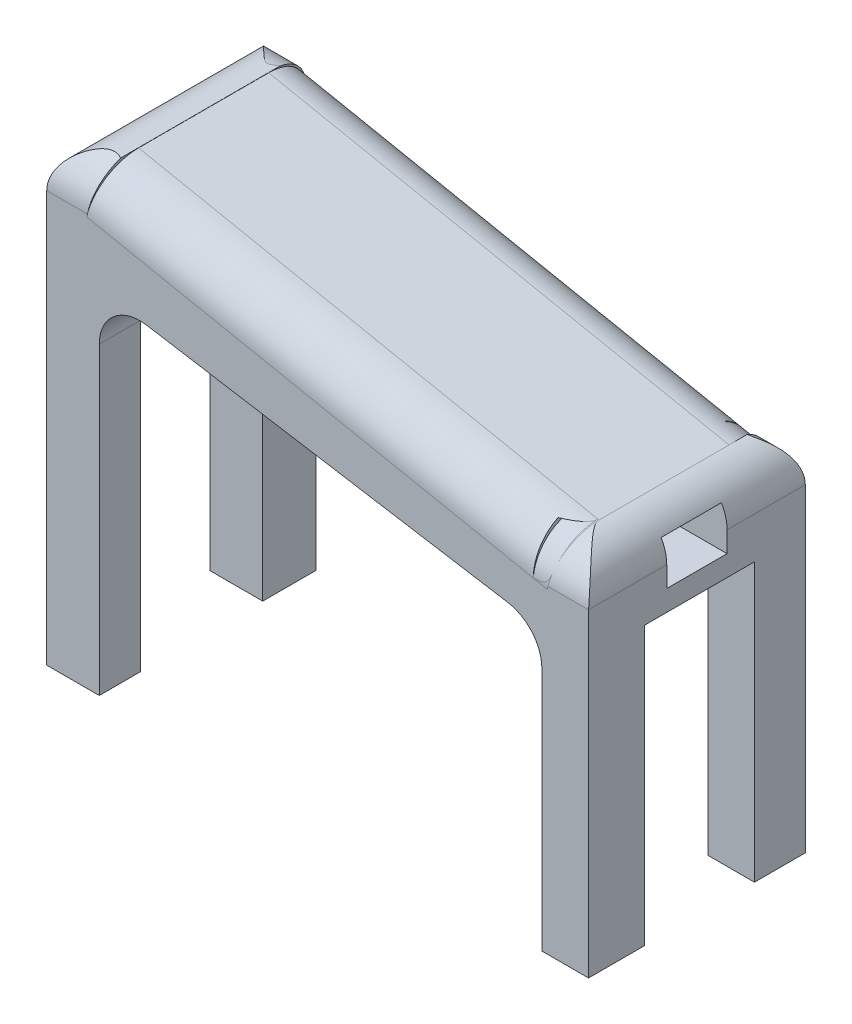
SolidWorks part; units mm, degrees
ref_plane "Alzado" through (0, 0, 0) normal (0, 0, 1) x (1, 0, 0)
ref_plane "Planta" through (0, 0, 0) normal (0, 1, 0) x (1, 0, 0)
ref_plane "Vista lateral" through (0, 0, 0) normal (1, 0, 0) x (0, 0, -1)
sketch "Croquis1" plane through (0, 0, 0) normal (0, 0, 1) x (1, 0, 0)
  line L0 (0, 0) -> (0, 1700) construction
  line L1 (0, 1700) -> (2000, 1300) construction
  line L2 (2000, 1300) -> (2000, 0) construction
  line L3 (2000, 0) -> (0, 0) construction
  line L4 (0, 0) -> (0, 1517.0294)
  line L5 (0, 0) -> (194.0414, 0)
  line L6 (194.0414, 0) -> (194.0414, 1123.2699)
  line L7 (368.4215, 1271.2753) -> (1702.0356, 1051.5962)
  line L8 (1827.6555, 903.5908) -> (1827.6555, 0)
  line L9 (1827.6555, 0) -> (2000, 0)
  line L10 (2000, 0) -> (2000, 1177.0294)
  line L11 (1879.4174, 1324.1165) -> (179.4174, 1664.1165)
  arc A0 (194.0414, 1123.2699) -> (368.4215, 1271.2753) centre (344.0414, 1123.2699) cw
  arc A1 (1702.0356, 1051.5962) -> (1827.6555, 903.5908) centre (1677.6555, 903.5908) cw
  arc A2 (2000, 1177.0294) -> (1879.4174, 1324.1165) centre (1850, 1177.0294) ccw
  arc A3 (0, 1517.0294) -> (179.4174, 1664.1165) centre (150, 1517.0294) cw
  dimension "D4" = 150
  dimension "D5" = 150
  dimension "D1" = 2000
  dimension "D2" = 1700
  dimension "D3" = 1300
extrude "Saliente-Extruir1" add sketch "Croquis1" along normal blind 800
sketch "Croquis2" plane through (0, 0, 0) normal (-1, 0, 0) x (0, 0, 1)
  line L0 (196.729, 0) -> (196.729, 1153.2045)
  line L1 (800, 0) -> (0, 0) construction
  line L2 (196.729, 1153.2045) -> (647.621, 1153.2045)
  line L3 (647.621, 1153.2045) -> (647.621, 0)
  line L4 (647.621, 0) -> (196.729, 0)
  line L5 (196.729, 0) -> (162.9375, 1.4667)
  point P4 (647.621, 0)
  point P8 (196.729, 0)
  line M2 (0, 0) -> (800, 0)
extrude "Cortar-Extruir1" cut sketch "Croquis2" against normal blind 479 contours L3 L2 L0 M2
sketch "Croquis6" plane through (326.9231, 1634.6154, 0) normal (0.1961, 0.9806, 0) x (0.9806, -0.1961, 0)
  line L0 (-150.4268, -800) -> (1583.2398, -800)
  line L1 (1583.2398, -800) -> (1583.2398, 0)
  line L2 (1583.2398, 0) -> (-150.4268, 0)
  line L3 (-150.4268, 0) -> (-150.4268, -800)
extrude "Cortar-Extruir4" cut sketch "Croquis6" against normal blind 1
fillet "Redondeo1" radius 160 2 edges at (1029.2213, 1493.1359, 0) (1029.2213, 1493.1359, 800)
sketch "Croquis7" plane through (0, 0, 0) normal (-1, 0, 0) x (0, 0, 1)
  line L0 (800, 1517.0294) -> (0, 1517.0294)
  line L1 (0, 1517.0294) -> (0, 0) construction
  line L2 (800, 1517.0294) -> (0, 1517.0294) construction
  line L3 (800, 1667.0294) -> (0, 1667.0294) construction
  line L4 (136.7582, 1667.0294) -> (699.6404, 1667.0294)
  line L5 (800, 1667.0294) -> (800, 1517.0294)
  line L6 (699.6404, 1667.0294) -> (800, 1667.0294)
  line L7 (0, 1517.0294) -> (0, 1667.0294)
  line L8 (0, 1667.0294) -> (136.7582, 1667.0294)
  arc A0 (0, 1517.0294) -> (136.7582, 1667.0294) centre (150.6411, 1517.0294) cw
  arc A1 (800, 1517.0294) -> (699.6404, 1667.0294) centre (637.7233, 1517.0294) ccw
extrude "Cortar-Extruir5" cut sketch "Croquis7" against normal blind 204 contours L7 A0 L8 | A1 L5 L6
sketch "Croquis8" plane through (2000, 0, 0) normal (1, 0, 0) x (0, 0, -1)
  line L0 (-800, 1177.0294) -> (0, 1177.0294)
  line L1 (-93.8376, 1324.1165) -> (-640, 1324.1165)
  line L2 (-640, 1663.1359) -> (-640, 1323.1359) construction
  line L3 (-800, 1324.1165) -> (0, 1324.1165) construction
  line L4 (-800, 1177.0294) -> (-800, 1324.1165)
  line L5 (-800, 1324.1165) -> (-640, 1324.1165)
  line L6 (0, 1177.0294) -> (0, 1324.1165)
  line L7 (0, 1324.1165) -> (-93.8376, 1324.1165)
  arc A0 (0, 1177.0294) -> (-93.8376, 1324.1165) centre (-162.1957, 1177.0294) ccw
  arc A1 (-640, 1324.1165) -> (-800, 1177.0294) centre (-640, 1163.5497) ccw
extrude "Cortar-Extruir6" cut sketch "Croquis8" against normal blind 204 contours A1 L5 L4 | A0 L6 L7
ref_plane "Plano1" through (297.3095, 1486.5477, 0) normal (0.1961, 0.9806, 0) x (0.9806, -0.1961, 0)
sketch "Croquis9" plane through (297.3095, 1486.5477, 0) normal (0.1961, 0.9806, 0) x (0.9806, -0.1961, 0)
  line L1 (1542.3555, -303.2342) -> (-1.3508, -303.2342)
  line L2 (1542.3555, -303.2342) -> (1542.3555, -499.1285)
  line L3 (1542.3555, -499.1285) -> (-1.3508, -499.1285)
  line L4 (-1.3508, -303.2342) -> (-1.3508, -499.1285)
  line L5 (1542.3555, -303.2342) -> (-1.3508, -499.1285) construction
  line L6 (1542.3555, -499.1285) -> (-1.3508, -303.2342) construction
  point P0 (770.5024, -401.1813)
  point P5 (770.5024, -401.1813)
extrude "Cortar-Extruir7" cut sketch "Croquis9" against normal blind 73
sketch "Croquis10" plane through (2000, 0, 0) normal (1, 0, 0) x (0, 0, -1)
  line L0 (-800, 0) -> (0, 0) construction
  line L1 (-594.427, 1024.2883) -> (-187.6288, 1024.2883)
  line L2 (-594.427, 1024.2883) -> (-594.427, 0)
  line L3 (-594.427, 0) -> (-187.6288, 0)
  line L4 (-187.6288, 1024.2883) -> (-187.6288, 0)
  line L5 (-594.427, 1024.2883) -> (-187.6288, 0) construction
  line L6 (-594.427, 0) -> (-187.6288, 1024.2883) construction
  point P0 (-391.0279, 512.1442)
  point P5 (-510.8751, 0)
  point P8 (-187.6288, 0)
  point P9 (-594.427, 0)
extrude "Cortar-Extruir8" cut sketch "Croquis10" against normal blind 204
sketch "Croquis11" plane through (0, 0, 0) normal (-1, 0, 0) x (0, 0, 1)
  line L1 (262.5884, 1609.5959) -> (579.3154, 1609.5959)
  line L2 (262.5884, 1609.5959) -> (262.5884, 1491.1811)
  line L3 (262.5884, 1491.1811) -> (579.3154, 1491.1811)
  line L4 (579.3154, 1609.5959) -> (579.3154, 1491.1811)
  line L5 (262.5884, 1609.5959) -> (579.3154, 1491.1811) construction
  line L6 (262.5884, 1491.1811) -> (579.3154, 1609.5959) construction
  point P0 (420.9519, 1550.3885)
  point P5 (420.9519, 1550.3885)
extrude "Cortar-Extruir9" cut sketch "Croquis11" against normal blind 204
sketch "Croquis13" plane through (2000, 0, 0) normal (1, 0, 0) x (0, 0, -1)
  line L0 (-800, 1177.0294) -> (0, 1177.0294) construction
  line L1 (-511.3483, 1253.3107) -> (-288.6517, 1253.3107)
  line L2 (-511.3483, 1253.3107) -> (-511.3483, 1100.7481)
  line L3 (-511.3483, 1100.7481) -> (-288.6517, 1100.7481)
  line L4 (-288.6517, 1253.3107) -> (-288.6517, 1100.7481)
  line L5 (-511.3483, 1253.3107) -> (-288.6517, 1100.7481) construction
  line L6 (-511.3483, 1100.7481) -> (-288.6517, 1253.3107) construction
  point P0 (-400, 1177.0294)
extrude "Cortar-Extruir10" cut sketch "Croquis13" against normal blind 204
